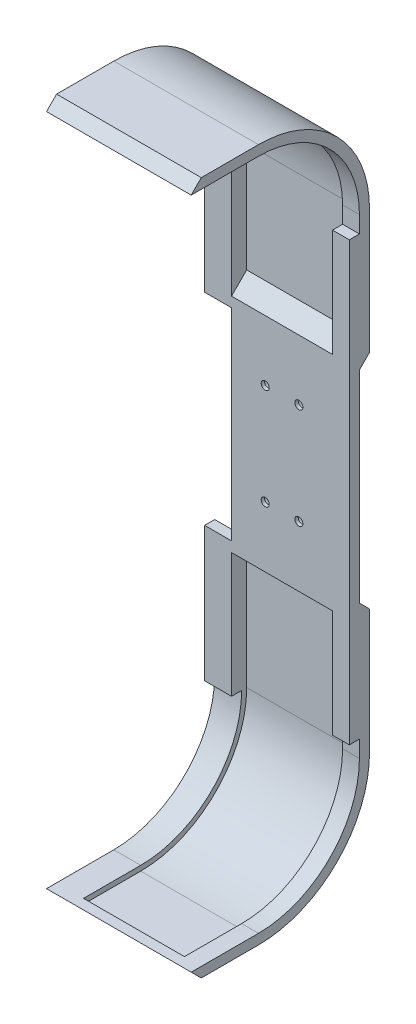
SolidWorks part; units mm, degrees
ref_plane "前视基准面" through (0, 0, 0) normal (0, 0, 1) x (1, 0, 0)
ref_plane "上视基准面" through (0, 0, 0) normal (0, 1, 0) x (1, 0, 0)
ref_plane "右视基准面" through (0, 0, 0) normal (1, 0, 0) x (0, 0, -1)
sketch "草图1" plane through (0, 0, 0) normal (0, 0, 1) x (1, 0, 0)
  line L61 (-143.75, 30) -> (-143.75, 70)
  line L65 (-135.75, 30) -> (-143.75, 30)
  line L80 (-105.75, 65) -> (-105.75, 70)
  line L81 (-143.75, 70) -> (-105.75, 70)
  line L82 (-105.75, 65) -> (-100.25, 65)
  line L83 (-100.25, 65) -> (-100.25, 70)
  line L84 (-100.25, 70) -> (99.75, 70)
  line L85 (-135.75, 30) -> (-135.75, -30)
  line L87 (143.25, -30) -> (143.25, -70)
  line L89 (99.75, 65) -> (99.75, 70)
  line L90 (105.25, 65) -> (99.75, 65)
  line L92 (105.25, 65) -> (105.25, 70)
  line L96 (105.25, -65) -> (105.25, -70)
  line L97 (143.25, -70) -> (105.25, -70)
  line L98 (105.25, -65) -> (99.75, -65)
  line L99 (99.75, -65) -> (99.75, -70)
  line L100 (-100.25, -70) -> (99.75, -70)
  line L101 (-100.25, -65) -> (-100.25, -70)
  line L102 (-105.75, -65) -> (-100.25, -65)
  line L103 (-143.75, -70) -> (-105.75, -70)
  line L104 (-105.75, -65) -> (-105.75, -70)
  line L105 (-135.75, -30) -> (-143.75, -30)
  line L106 (-143.75, -30) -> (-143.75, -70)
  line L107 (143.25, 30) -> (143.25, 70)
  line L108 (105.25, 70) -> (143.25, 70)
  line L109 (143.25, 30) -> (135.25, 30)
  line L110 (135.25, 30) -> (135.25, -30)
  line L111 (135.25, -30) -> (143.25, -30)
  point P9 (-0.25, 70)
  point P27 (-135.75, 0)
  point P35 (0, -70)
extrude "凸台-拉伸1" add sketch "草图1" along normal blind 3
ref_plane "基准面1" through (-143.75, 0, 0) normal (-1, 0, 0) x (0, 0, 1)
sketch "草图2" plane through (-143.75, 0, 0) normal (-1, 0, 0) x (0, 0, 1)
  line L1 (0, 70) -> (0, 30)
  line L2 (0, 30) -> (-3, 33)
  line L3 (-3, 33) -> (-3, 70)
  line L4 (50, 100) -> (47, 103)
  line L8 (30, 103) -> (47, 103)
  line L17 (45, 90) -> (50, 100)
  line L18 (45, 90) -> (60, 90)
  line L19 (60, 90) -> (60, 87)
  line L20 (60, 87) -> (41, 87)
  line L21 (41, 87) -> (47, 100)
  line L22 (30, 100) -> (47, 100)
  line L24 (30, -100) -> (47, -100)
  line L25 (41, -87) -> (47, -100)
  line L26 (60, -87) -> (41, -87)
  line L27 (60, -90) -> (60, -87)
  line L28 (45, -90) -> (60, -90)
  line L29 (45, -90) -> (50, -100)
  line L30 (30, -103) -> (47, -103)
  line L31 (50, -100) -> (47, -103)
  line L32 (-3, -33) -> (-3, -70)
  line L33 (0, -30) -> (-3, -33)
  line L34 (0, -70) -> (0, -30)
  arc A0 (0, 70) -> (30, 100) centre (30, 70) cw
  arc A1 (-3, 70) -> (30, 103) centre (30, 70) cw
  arc A4 (-3, -70) -> (30, -103) centre (30, -70) ccw
  arc A5 (0, -70) -> (30, -100) centre (30, -70) ccw
extrude "凸台-拉伸2" add sketch "草图2" against normal blind 287
sketch "草图4" plane through (-143.75, 0, 0) normal (-1, 0, 0) x (0, 0, 1)
  line L1 (30, 100) -> (47, 100) construction
  line L4 (60.2366, -100) -> (38.5, -100)
  line L5 (60.2366, -100) -> (60.2366, 100)
  line L6 (60.2366, 100) -> (38.5, 100)
  line L7 (38.5, -100) -> (38.5, 100)
extrude "切除-拉伸1" cut sketch "草图4" against normal blind 43
ref_plane "基准面2" through (143.25, 0, 0) normal (1, 0, 0) x (0, 0, -1)
sketch "草图5" plane through (143.25, 0, 0) normal (1, 0, 0) x (0, 0, -1)
  line L1 (-30, 100) -> (-47, 100) construction
  line L4 (-63.1672, -100) -> (-39.752, -100)
  line L5 (-63.1672, -100) -> (-63.1672, 100)
  line L6 (-63.1672, 100) -> (-39.752, 100)
  line L7 (-39.752, -100) -> (-39.752, 100)
extrude "切除-拉伸2" cut sketch "草图5" against normal blind 43
sketch "草图6" plane through (0, 0, 0) normal (0, 0, 1) x (1, 0, 0)
  line L0 (-100.75, 103) -> (203.0936, 103)
  line L3 (143.25, 103) -> (-143.75, 103) construction
  line L7 (-100.75, 103) -> (-100.75, -103)
  line L8 (143.25, -103) -> (-143.75, -103) construction
  line L9 (-100.75, -103) -> (203.0936, -103)
  line L10 (203.0936, -103) -> (203.0936, 103)
extrude "切除-拉伸6" cut sketch "草图6" against normal blind 100 and the other way blind 100
hole_wizard "大小六角凹头盖螺钉柱孔1" positions "草图7" profile "草图8" counterbore size "M2" standard "AS" end condition through all
sketch "草图7" plane through (0, 0, 0) normal (0, 0, -1) x (-1, 0, 0)
  point P18 (115.75, 15)
  point P20 (125.75, 15)
  point P28 (125.75, -15)
  point P32 (115.75, -15)
sketch "草图8" plane through (-115.75, 15, 0) normal (1, 0, 0) x (0, 1, 0)
  line L0 (0, 0) -> (0, 50)
  line L1 (0, 50) -> (1.2, 50)
  line L3 (1.2, 50) -> (1.2, 2)
  line L4 (2.15, 2) -> (1.2, 2)
  line L5 (2.15, 2) -> (2.15, 0.0241)
  line L6 (2.15, 0.0241) -> (2.175, 0)
  line L7 (2.175, 0) -> (0, 0)
  line L8 (-2.15, 0.0241) -> (-2.175, 0) construction
  line L11 (0, -6.35) -> (0, 107.95) construction
  dimension "通孔孔直径" = 2.4
  dimension "通孔孔深度" = 50
  dimension "柱形沉头孔直径" = 4.3
  dimension "柱形沉头孔深度" = 2
  dimension "近端锥形沉头孔直径" = 4.35
  dimension "近端锥形沉头孔角度" = 92
ref_plane "基准面3" through (-135.75, 0, 0) normal (-1, 0, 0) x (0, 0, 1)
sketch "草图10" plane through (-135.75, 0, 0) normal (-1, 0, 0) x (0, 0, 1)
  line L0 (30, 100) -> (47, 100)
  line L1 (30, 100) -> (50, 100) construction
  line L2 (3, 70) -> (0, 70) construction
  line L3 (30, 101.5) -> (45.5, 101.5)
  line L4 (45.5, 101.5) -> (47, 100)
  line L5 (0, 70) -> (3, 70)
  line L6 (3, 70) -> (3, 33)
  line L7 (3, 70) -> (3, 30) construction
  line L8 (3, 33) -> (-1.5, 37.5)
  line L9 (-1.5, 37.5) -> (-1.5, 70)
  line L11 (-1.5, -37.5) -> (-1.5, -70)
  line L12 (3, -33) -> (-1.5, -37.5)
  line L13 (3, -70) -> (3, -33)
  line L14 (0, -70) -> (3, -70)
  line L15 (45.5, -101.5) -> (47, -100)
  line L16 (30, -101.5) -> (45.5, -101.5)
  line L17 (30, -100) -> (47, -100)
  arc A0 (30, 100) -> (0, 70) centre (30, 70) ccw
  arc A1 (30, 101.5) -> (-1.5, 70) centre (30, 70) ccw
  arc A2 (30, -101.5) -> (-1.5, -70) centre (30, -70) cw
  arc A3 (30, -100) -> (0, -70) centre (30, -70) cw
extrude "切除-拉伸7" cut sketch "草图10" against normal blind 30
